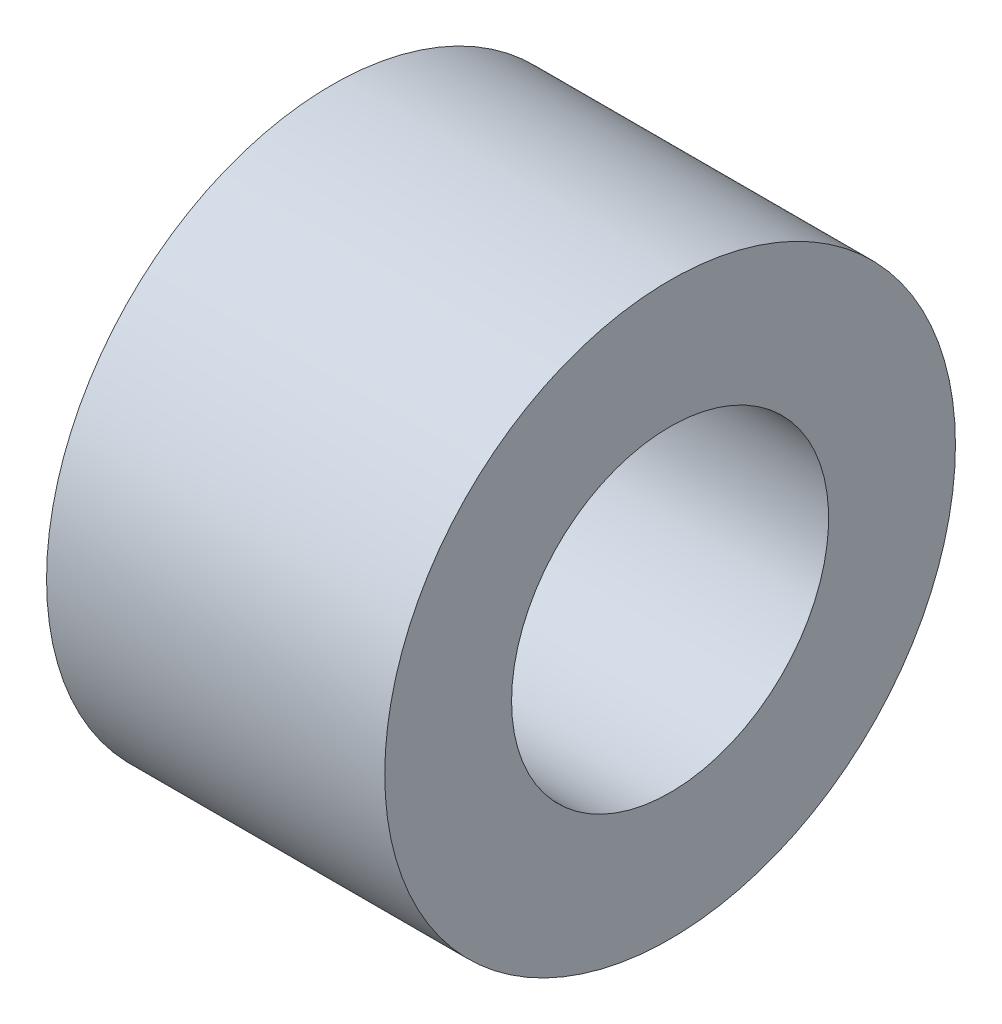
SolidWorks part; units mm, degrees
material "Резина"
ref_plane "Спереди" through (0, 0, 0) normal (0, 0, 1) x (1, 0, 0)
ref_plane "Сверху" through (0, 0, 0) normal (0, 1, 0) x (1, 0, 0)
ref_plane "Справа" through (0, 0, 0) normal (1, 0, 0) x (0, 0, -1)
sketch "Эскиз1" plane through (0, 0, 0) normal (0, 0, 1) x (1, 0, 0)
  line L0 (0, 37.5) -> (80, 37.5)
  line L1 (0, 0) -> (80, 0) construction
  line L2 (0, 37.5) -> (0, 67.5)
  line L3 (0, 67.5) -> (80, 67.5)
  line L4 (80, 37.5) -> (80, 67.5)
  dimension "D1" = 80
  dimension "D2" = 67.5
  dimension "D3" = 75
revolve "Повернуть1" add sketch "Эскиз1" angle 360 about L1
